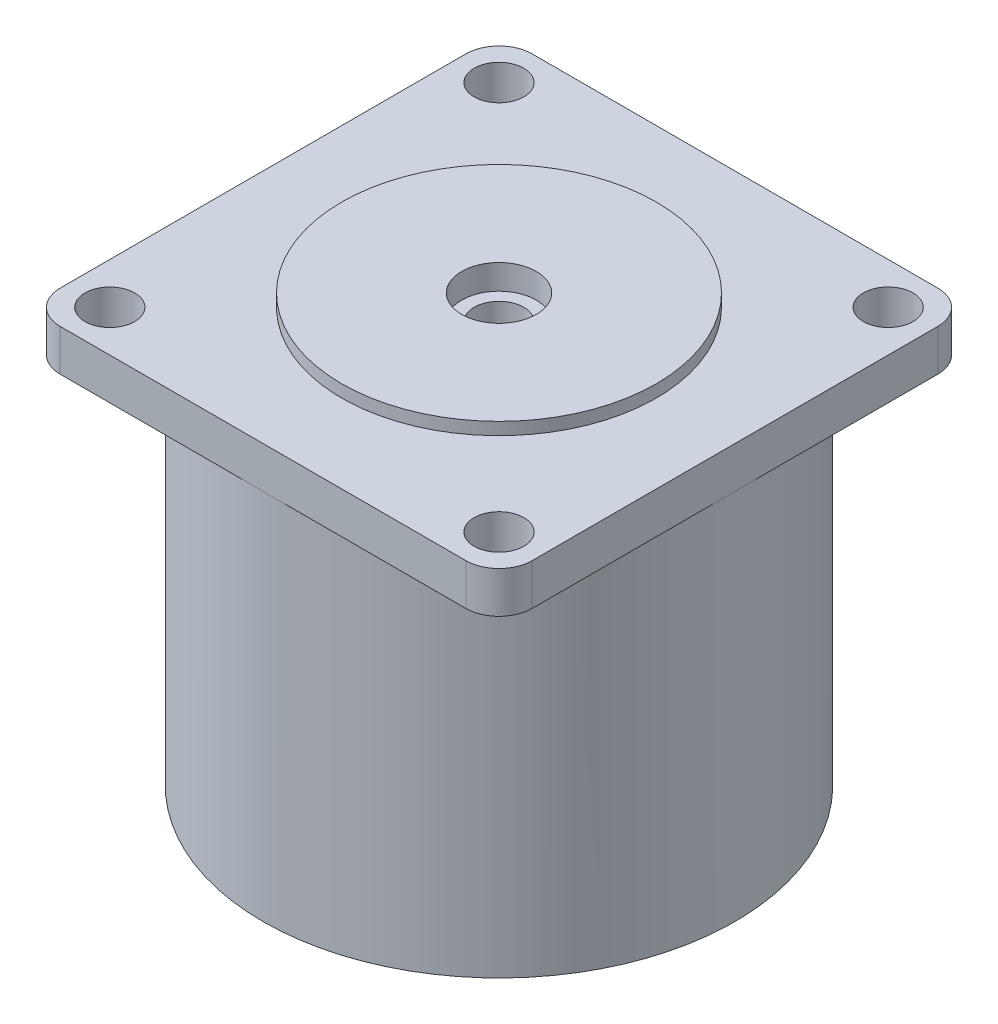
SolidWorks part; units mm, degrees
ref_plane "Front Plane" through (0, 0, 0) normal (0, 0, 1) x (1, 0, 0)
ref_plane "Top Plane" through (0, 0, 0) normal (0, 1, 0) x (1, 0, 0)
ref_plane "Right Plane" through (0, 0, 0) normal (1, 0, 0) x (0, 0, -1)
sketch "Sketch1" plane through (0, 0, 0) normal (0, 1, 0) x (1, 0, 0)
  line L1 (-28.5, 0) -> (-28.5, 28.5)
  line L2 (-28.5, 28.5) -> (28.5, 28.5)
  line L3 (28.5, 28.5) -> (28.5, -28.5)
  line L4 (28.5, -28.5) -> (-28.5, -28.5)
  line L5 (-28.5, -28.5) -> (-28.5, 0)
extrude "Boss-Extrude1" add sketch "Sketch1" along normal blind 5
fillet "Fillet1" radius 4 4 edges at (28.5, 2.5, 28.5) (28.5, 2.5, -28.5) (-28.5, 2.5, -28.5) (-28.5, 2.5, 28.5)
sketch "Sketch2" plane through (0, 5, 0) normal (0, 1, 0) x (1, 0, 0)
  circle A0 centre (-23.5, 23.5) radius 3
  circle A1 centre (23.5, 23.5) radius 3
  circle A2 centre (23.5, -23.5) radius 3
  circle A3 centre (-23.5, -23.5) radius 3
extrude "Cut-Extrude1" cut sketch "Sketch2" against normal through all
sketch "Sketch3" plane through (0, 0, 0) normal (0, -1, 0) x (1, 0, 0)
  circle A0 centre (0, 0) radius 28.5
extrude "Boss-Extrude2" add sketch "Sketch3" along normal blind 45
sketch "Sketch4" plane through (0, 5, 0) normal (0, 1, 0) x (1, 0, 0)
  circle A0 centre (0, 0) radius 19
extrude "Boss-Extrude3" add sketch "Sketch4" along normal blind 1.5
sketch "Sketch5" plane through (0, 6.5, 0) normal (0, 1, 0) x (1, 0, 0)
  circle A0 centre (0, 0) radius 4.5
extrude "Cut-Extrude2" cut sketch "Sketch5" against normal blind 3
sketch "Sketch6" plane through (0, 3.5, 0) normal (0, 1, 0) x (1, 0, 0)
  circle A0 centre (0, 0) radius 3
extrude "Cut-Extrude3" cut sketch "Sketch6" against normal through all
